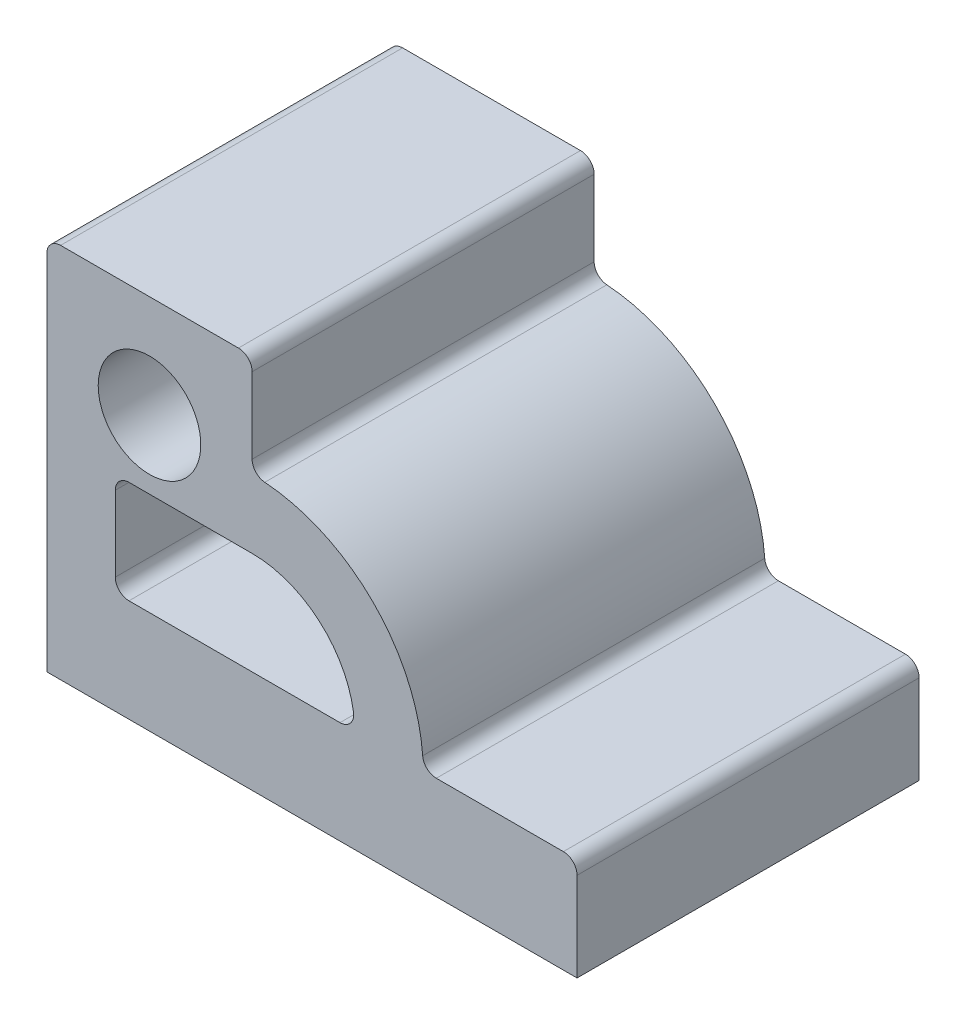
SolidWorks part; units mm, degrees
ref_plane "Front Plane" through (0, 0, 0) normal (0, 0, 1) x (1, 0, 0)
ref_plane "Top Plane" through (0, 0, 0) normal (0, 1, 0) x (1, 0, 0)
ref_plane "Right Plane" through (0, 0, 0) normal (1, 0, 0) x (0, 0, -1)
sketch "Sketch1" plane through (0, 0, 0) normal (0, 0, 1) x (1, 0, 0)
  line L0 (70.1343, 0) -> (-84.8657, 0)
  line L1 (-84.8657, 0) -> (-84.8657, 106)
  line L2 (-80.8657, 110) -> (-28.8657, 110)
  line L3 (-24.8657, 106) -> (-24.8657, 83.8516)
  line L4 (28.9859, 30) -> (66.1343, 30)
  line L5 (70.1343, 26) -> (70.1343, 0)
  line L6 (0.8248, 30) -> (-60.8657, 30)
  line L7 (-64.8657, 34) -> (-64.8657, 56)
  line L8 (-60.8657, 60) -> (-24.8657, 60)
  arc A0 (-21.162, 79.8626) -> (24.9969, 33.7037) centre (-24.8657, 30) cw
  arc A1 (-24.8657, 60) -> (4.7771, 34.6154) centre (-24.8657, 30) cw
  circle A2 centre (-54.8657, 80) radius 15
  arc A3 (0.8248, 30) -> (4.7771, 34.6154) centre (0.8248, 34) ccw
  arc A4 (-24.8657, 83.8516) -> (-21.162, 79.8626) centre (-20.8657, 83.8516) ccw
  arc A5 (24.9969, 33.7037) -> (28.9859, 30) centre (28.9859, 34) ccw
  arc A6 (66.1343, 30) -> (70.1343, 26) centre (66.1343, 26) cw
  arc A7 (-28.8657, 110) -> (-24.8657, 106) centre (-28.8657, 106) cw
  arc A8 (-84.8657, 106) -> (-80.8657, 110) centre (-80.8657, 106) cw
  arc A9 (-60.8657, 30) -> (-64.8657, 34) centre (-60.8657, 34) cw
  arc A10 (-64.8657, 56) -> (-60.8657, 60) centre (-60.8657, 56) cw
  point P16 (0, 0)
  point P17 (0, 0)
  point P18 (0, 0)
  point P19 (0, 0)
  point P20 (-87.5558, 110.5496)
  point P21 (0, 0)
  point P22 (0, 0)
  point P31 (70.1343, 30)
  point P34 (-24.8657, 110)
  point P37 (-84.8657, 110)
  point P40 (-64.8657, 30)
  point P43 (-64.8657, 60)
  dimension "D5" = 50
  dimension "D6" = 30
  dimension "D11" = 30
  dimension "D12" = 4
  dimension "D1" = 155
  dimension "D2" = 30
  dimension "D3" = 110
  dimension "D4" = 60
  dimension "D7" = 30
  dimension "D8" = 40
  dimension "D9" = 30
  dimension "D10" = 30
extrude "Boss-Extrude1" add sketch "Sketch1" along normal blind 100
